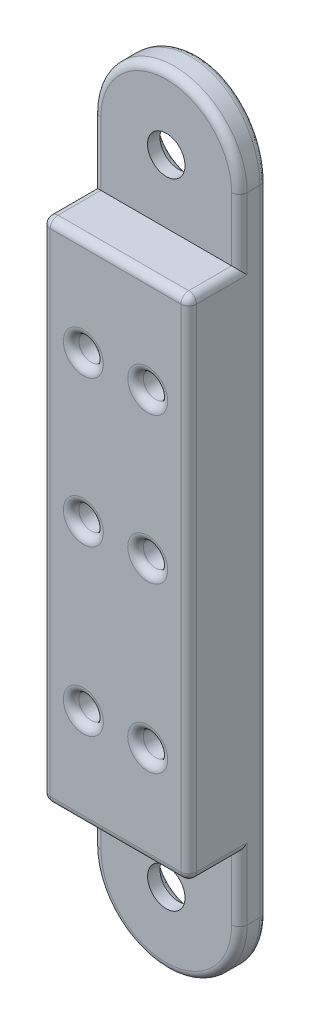
SolidWorks part; units mm, degrees
material "Nylon 101"
ref_plane "Front Plane" through (0, 0, 0) normal (0, 0, 1) x (1, 0, 0)
ref_plane "Top Plane" through (0, 0, 0) normal (0, 1, 0) x (1, 0, 0)
ref_plane "Right Plane" through (0, 0, 0) normal (1, 0, 0) x (0, 0, -1)
sketch "Sketch1" plane through (0, 0, 0) normal (0, 1, 0) x (1, 0, 0)
  line L1 (-4.1913, 1.27) -> (5.3337, 1.27)
  line L2 (-4.1913, 1.27) -> (-4.1913, 6.35)
  line L4 (5.3337, 1.27) -> (5.3337, 6.35)
  arc A0 (-4.1913, 6.35) -> (5.3337, 6.35) centre (0.5712, -31.4512) cw
  dimension "D3" = 38.1
  dimension "D1" = 9.525
  dimension "D2" = 5.08
extrude "Main profile" add sketch "Sketch1" along normal blind 50.8
sketch "Sketch2" plane through (0, 0, -1.27) normal (0, 0, 1) x (1, 0, 0)
  line L0 (-4.1913, 50.8) -> (-4.1913, 0) construction
  line L1 (5.3337, 50.8) -> (5.3337, 0) construction
  line L2 (-4.1913, 50.8) -> (5.3337, 50.8) construction
  line L3 (-4.1913, 0) -> (5.3337, 0) construction
  line L4 (-4.1913, 46.0375) -> (-4.1913, 4.7625)
  line L5 (5.3337, 46.0375) -> (5.3337, 4.7625)
  line L10 (-4.1913, 0) -> (5.3337, 0)
  line L11 (5.3337, 0) -> (5.3337, 50.8)
  line L12 (5.3337, 50.8) -> (-4.1913, 50.8)
  line L13 (-4.1913, 50.8) -> (-4.1913, 0)
  line L14 (-4.1913, 0) -> (5.3337, 0)
  line L15 (5.3337, 0) -> (5.3337, 50.8)
  line L16 (5.3337, 50.8) -> (-4.1913, 50.8)
  line L17 (-4.1913, 50.8) -> (-4.1913, 0)
  arc A0 (-4.1913, 46.0375) -> (5.3337, 46.0375) centre (0.5712, 46.0375) cw
  arc A1 (5.3337, 4.7625) -> (-4.1913, 4.7625) centre (0.5712, 4.7625) cw
  line M9 (-4.1913, 0) -> (5.3337, 0)
  line M10 (5.3337, 0) -> (5.3337, 50.8)
  line M11 (5.3337, 50.8) -> (-4.1913, 50.8)
  line M12 (-4.1913, 50.8) -> (-4.1913, 0)
  dimension "D2" = 4.7625
  dimension "D1" = 0
extrude "End rounds" cut sketch "Sketch2" against normal blind 25.4 contours A0 L16 M12 | A0 M11 M10 | A1 L14 M10 | A1 M9 M12
sketch "Sketch3" plane through (-4.1913, 0, 0) normal (-1, 0, 0) x (0, 0, 1)
  line L1 (-1.27, 46.0375) -> (-1.27, 50.8) construction
  line L4 (-1.27, 4.7625) -> (-1.27, 46.0375)
  line L7 (-1.27, 46.0375) -> (-6.35, 46.0375)
  line L8 (-1.27, 4.7625) -> (-1.27, 46.0375)
  line L12 (-1.27, 0) -> (-1.27, 4.7625) construction
  line L14 (-4.572, 25.4) -> (-1.27, 25.4) construction
  line L15 (-1.27, 46.0375) -> (-1.27, 50.8)
  line L17 (-4.572, 41.91) -> (-1.27, 41.91)
  line L18 (-1.27, 0) -> (-1.27, 4.7625)
  line L19 (-1.27, 8.89) -> (-4.572, 8.89)
  line L20 (-2.921, 8.89) -> (-2.921, 41.91) construction
  line L21 (-1.27, 50.8) -> (-4.572, 50.8)
  line L22 (-1.27, 50.8) -> (-1.27, 0)
  line L23 (-1.27, 0) -> (-4.572, 0)
  line L24 (-4.572, 50.8) -> (-4.572, 0)
  line L29 (-6.35, 4.7625) -> (-1.27, 4.7625)
  line L31 (-6.35, 46.0375) -> (-6.35, 4.7625)
  line L32 (-6.35, 46.0375) -> (-6.35, 4.7625)
  spline S0 degree 2 poles (-6.6488, 50.8) (-6.35, 48.4094) (-6.35, 46.0375) knots 0 0 0 0.468627 0.468627 0.468627 weights 0.033338 0.035569 0.037801 construction
  spline S1 degree 2 poles (-6.35, 4.7625) (-6.35, 2.3906) (-6.6488, 0) knots 0.468627 0.468627 0.468627 1 1 1 weights 0.037801 0.040332 0.042863 construction
  spline S2 degree 2 poles (-6.6488, 50.8) (-6.35, 48.4094) (-6.35, 46.0375) knots 0 0 0 0.468627 0.468627 0.468627 weights 0.033338 0.035569 0.037801
  spline S3 degree 2 poles (-6.35, 4.7625) (-6.35, 2.3906) (-6.6488, 0) knots 0.468627 0.468627 0.468627 1 1 1 weights 0.037801 0.040332 0.042863
  point P19 (-2.921, 25.4)
  line M11 (-1.27, 4.7625) -> (-1.27, 46.0375)
  line M12 (-1.27, 46.0375) -> (-6.35, 46.0375)
  line M14 (-6.35, 4.7625) -> (-1.27, 4.7625)
  dimension "D2" = 3.302
  dimension "D3" = 8.89
  dimension "D1" = 0
extrude "Locating Flange" cut sketch "Sketch3" against normal through all contours L24 L23 L18 M14 | L19 L24 M14 M11 | L24 L17 L8 M12 | L21 L24 L15 M12
ref_plane "Top Surface" through (0, 0, -6.6488) normal (0, 0, -1) x (-1, 0, 0)
sketch "Sketch4" plane through (0, 0, -6.6488) normal (0, 0, -1) x (-1, 0, 0)
  line L0 (-0.5712, 18.542) -> (-0.5712, 32.258) construction
  line L1 (-2.6827, 38.735) -> (1.5403, 38.735)
  line L2 (-5.3337, 46.0375) -> (-5.3337, 4.7625)
  line L6 (-3.8097, 37.608) -> (-3.8097, 33.385)
  line L7 (-2.6827, 32.258) -> (1.5403, 32.258)
  line L8 (2.6673, 37.608) -> (2.6673, 33.385)
  line L9 (-2.6827, 29.226) -> (1.5403, 29.226)
  line L14 (-3.8097, 28.099) -> (-3.8097, 23.876)
  line L16 (-2.6827, 22.749) -> (1.5403, 22.749)
  line L18 (4.1913, 8.89) -> (4.1913, 41.91)
  line L19 (-5.3337, 8.89) -> (4.1913, 8.89)
  line L20 (-5.3337, 41.91) -> (-5.3337, 8.89)
  line L21 (4.1913, 41.91) -> (-5.3337, 41.91)
  line L22 (4.1913, 8.89) -> (4.1913, 41.91)
  line L23 (-5.3337, 8.89) -> (4.1913, 8.89)
  line L24 (-5.3337, 41.91) -> (-5.3337, 8.89)
  line L25 (4.1913, 41.91) -> (-5.3337, 41.91)
  line L26 (2.6673, 28.099) -> (2.6673, 23.876)
  line L27 (-2.6827, 18.542) -> (1.5403, 18.542)
  line L28 (-3.8097, 17.415) -> (-3.8097, 13.192)
  line L29 (-2.6827, 12.065) -> (1.5403, 12.065)
  line L30 (2.6673, 17.415) -> (2.6673, 13.192)
  line L31 (-5.3337, 25.4) -> (4.1913, 25.4) construction
  line L34 (-5.3337, 46.0375) -> (-5.3337, 4.7625)
  line L36 (4.1913, 4.7625) -> (4.1913, 46.0375)
  line L37 (4.1913, 4.7625) -> (4.1913, 46.0375)
  arc A0 (1.5403, 12.065) -> (2.6673, 13.192) centre (1.5403, 13.192) ccw
  arc A1 (-3.8097, 13.192) -> (-2.6827, 12.065) centre (-2.6827, 13.192) ccw
  arc A2 (4.1913, 46.0375) -> (-5.3337, 46.0375) centre (-0.5712, 46.0375) ccw
  arc A3 (4.1913, 46.0375) -> (-5.3337, 46.0375) centre (-0.5712, 46.0375) ccw
  arc A6 (-5.3337, 4.7625) -> (4.1913, 4.7625) centre (-0.5712, 4.7625) ccw
  arc A7 (-5.3337, 4.7625) -> (4.1913, 4.7625) centre (-0.5712, 4.7625) ccw
  arc A8 (1.5403, 18.542) -> (2.6673, 17.415) centre (1.5403, 17.415) cw
  arc A9 (-2.6827, 18.542) -> (-3.8097, 17.415) centre (-2.6827, 17.415) ccw
  arc A10 (1.5403, 38.735) -> (2.6673, 37.608) centre (1.5403, 37.608) cw
  arc A11 (1.5403, 32.258) -> (2.6673, 33.385) centre (1.5403, 33.385) ccw
  arc A12 (-3.8097, 33.385) -> (-2.6827, 32.258) centre (-2.6827, 33.385) ccw
  arc A13 (1.5403, 22.749) -> (2.6673, 23.876) centre (1.5403, 23.876) ccw
  arc A14 (-2.6827, 29.226) -> (-3.8097, 28.099) centre (-2.6827, 28.099) ccw
  arc A15 (-3.8097, 23.876) -> (-2.6827, 22.749) centre (-2.6827, 23.876) ccw
  arc A16 (1.5403, 29.226) -> (2.6673, 28.099) centre (1.5403, 28.099) cw
  arc A17 (-2.6827, 38.735) -> (-3.8097, 37.608) centre (-2.6827, 37.608) ccw
  point P23 (-0.5712, 18.542)
  point P27 (-0.5712, 25.4)
  point P28 (-0.5712, 29.226)
  point P57 (-0.5712, 25.4)
  dimension "D6" = 1.127
  dimension "D4" = 3.175
  dimension "D5" = 3.175
  dimension "D7" = 6.477
  dimension "D1" = 0
  dimension "D3" = 0
extrude "Button Pockets" cut sketch "Sketch4" against normal blind 3.81 contours L16 L0 L9 L14 | L0 L16 L26 L9 | L30 L27 L28 L29 | L6 A12 L7 A11 L8 A10 L1 A17
sketch "Hole Locations" plane through (0, 0, -6.6488) normal (0, 0, -1) x (-1, 0, 0)
  line L2 (-5.3337, 46.0375) -> (-5.3337, 4.7625)
  line L6 (-5.3337, 46.0375) -> (-5.3337, 4.7625)
  line L8 (4.1913, 4.7625) -> (4.1913, 46.0375)
  line L9 (4.1913, 4.7625) -> (4.1913, 46.0375)
  arc A2 (4.1913, 46.0375) -> (-5.3337, 46.0375) centre (-0.5712, 46.0375) ccw
  arc A3 (-5.3337, 4.7625) -> (4.1913, 4.7625) centre (-0.5712, 4.7625) ccw
  arc A4 (4.1913, 46.0375) -> (-5.3337, 46.0375) centre (-0.5712, 46.0375) ccw
  arc A5 (-5.3337, 4.7625) -> (4.1913, 4.7625) centre (-0.5712, 4.7625) ccw
  point P5 (-0.5712, 46.0375)
  point P8 (-0.5712, 4.7625)
  dimension "D1" = 0
hole_wizard "CBORE for #2 Socket Head Cap Screw1" positions "Sketch7" profile "Sketch9" counterbore size "#2" standard "ANSI Inch" end condition through all
sketch "Sketch7" plane through (0, 0, -6.6488) normal (0, 0, -1) x (-1, 0, 0)
  point P0 (-0.5712, 46.0375)
  point P3 (-0.5712, 4.7625)
sketch "Sketch9" plane through (0.5712, 46.0375, -6.6488) normal (1, 0, 0) x (0, 1, 0)
  line L0 (0, 0) -> (0, 5.3788)
  line L1 (0, 5.3788) -> (1.2192, 5.3788)
  line L3 (1.2192, 5.3788) -> (1.2192, 1.27)
  line L4 (1.2192, 1.27) -> (2.286, 1.27)
  line L5 (2.286, 1.27) -> (2.286, 0)
  line L7 (2.286, 0) -> (0, 0)
  line L11 (0, -6.35) -> (0, 107.95) construction
  dimension "Thru Hole Dia." = 2.4384
  dimension "Thru Hole Depth" = 5.3788
  dimension "C'Bore Dia." = 4.572
  dimension "C'Bore Depth" = 1.27
sketch "Sketch13" plane through (0, 0, -1.27) normal (0, 0, 1) x (1, 0, 0)
  line L0 (-1.5403, 18.542) -> (2.6827, 18.542) construction
  line L1 (3.8097, 17.415) -> (3.8097, 13.192) construction
  line L2 (2.6827, 12.065) -> (-1.5403, 12.065) construction
  line L3 (-2.6673, 13.192) -> (-2.6673, 17.415) construction
  line L4 (-1.5403, 29.226) -> (2.6827, 29.226) construction
  line L5 (3.8097, 28.099) -> (3.8097, 23.876) construction
  line L6 (2.6827, 22.749) -> (-1.5403, 22.749) construction
  line L7 (-2.6673, 23.876) -> (-2.6673, 28.099) construction
  line L8 (3.8097, 37.608) -> (3.8097, 33.385) construction
  line L9 (2.6827, 32.258) -> (-1.5403, 32.258) construction
  line L10 (-2.6673, 33.385) -> (-2.6673, 37.608) construction
  line L11 (-1.5403, 38.735) -> (2.6827, 38.735) construction
  line L12 (-4.1913, 41.91) -> (-4.1913, 8.89) construction
  line L13 (-4.1913, 8.89) -> (5.3337, 8.89) construction
  line L14 (5.3337, 8.89) -> (5.3337, 41.91) construction
  line L15 (5.3337, 41.91) -> (-4.1913, 41.91) construction
  line L16 (-1.5403, 18.542) -> (2.6827, 18.542)
  line L17 (3.8097, 17.415) -> (3.8097, 13.192)
  line L18 (2.6827, 12.065) -> (-1.5403, 12.065)
  line L19 (-2.6673, 13.192) -> (-2.6673, 17.415)
  line L20 (-1.5403, 29.226) -> (2.6827, 29.226)
  line L21 (3.8097, 28.099) -> (3.8097, 23.876)
  line L22 (2.6827, 22.749) -> (-1.5403, 22.749)
  line L23 (-2.6673, 23.876) -> (-2.6673, 28.099)
  line L24 (3.8097, 37.608) -> (3.8097, 33.385)
  line L25 (2.6827, 32.258) -> (-1.5403, 32.258)
  line L26 (-2.6673, 33.385) -> (-2.6673, 37.608)
  line L27 (-1.5403, 38.735) -> (2.6827, 38.735)
  line L28 (-4.1913, 41.91) -> (-4.1913, 8.89)
  line L29 (-4.1913, 8.89) -> (5.3337, 8.89)
  line L30 (5.3337, 8.89) -> (5.3337, 41.91)
  line L31 (5.3337, 41.91) -> (-4.1913, 41.91)
  line L32 (-1.5243, 35.4965) -> (2.6667, 35.4965) construction
  arc A0 (3.8097, 17.415) -> (2.6827, 18.542) centre (2.6827, 17.415) ccw construction
  arc A1 (2.6827, 12.065) -> (3.8097, 13.192) centre (2.6827, 13.192) ccw construction
  arc A2 (-2.6673, 13.192) -> (-1.5403, 12.065) centre (-1.5403, 13.192) ccw construction
  arc A3 (-1.5403, 18.542) -> (-2.6673, 17.415) centre (-1.5403, 17.415) ccw construction
  arc A4 (-1.5403, 29.226) -> (-2.6673, 28.099) centre (-1.5403, 28.099) ccw construction
  arc A5 (3.8097, 28.099) -> (2.6827, 29.226) centre (2.6827, 28.099) ccw construction
  arc A6 (2.6827, 22.749) -> (3.8097, 23.876) centre (2.6827, 23.876) ccw construction
  arc A7 (-2.6673, 23.876) -> (-1.5403, 22.749) centre (-1.5403, 23.876) ccw construction
  arc A8 (3.8097, 37.608) -> (2.6827, 38.735) centre (2.6827, 37.608) ccw construction
  arc A9 (2.6827, 32.258) -> (3.8097, 33.385) centre (2.6827, 33.385) ccw construction
  arc A10 (-2.6673, 33.385) -> (-1.5403, 32.258) centre (-1.5403, 33.385) ccw construction
  arc A11 (-1.5403, 38.735) -> (-2.6673, 37.608) centre (-1.5403, 37.608) ccw construction
  arc A12 (3.8097, 17.415) -> (2.6827, 18.542) centre (2.6827, 17.415) ccw
  arc A13 (2.6827, 12.065) -> (3.8097, 13.192) centre (2.6827, 13.192) ccw
  arc A14 (-2.6673, 13.192) -> (-1.5403, 12.065) centre (-1.5403, 13.192) ccw
  arc A15 (-1.5403, 18.542) -> (-2.6673, 17.415) centre (-1.5403, 17.415) ccw
  arc A16 (-1.5403, 29.226) -> (-2.6673, 28.099) centre (-1.5403, 28.099) ccw
  arc A17 (3.8097, 28.099) -> (2.6827, 29.226) centre (2.6827, 28.099) ccw
  arc A18 (2.6827, 22.749) -> (3.8097, 23.876) centre (2.6827, 23.876) ccw
  arc A19 (-2.6673, 23.876) -> (-1.5403, 22.749) centre (-1.5403, 23.876) ccw
  arc A20 (3.8097, 37.608) -> (2.6827, 38.735) centre (2.6827, 37.608) ccw
  arc A21 (2.6827, 32.258) -> (3.8097, 33.385) centre (2.6827, 33.385) ccw
  arc A22 (-2.6673, 33.385) -> (-1.5403, 32.258) centre (-1.5403, 33.385) ccw
  arc A23 (-1.5403, 38.735) -> (-2.6673, 37.608) centre (-1.5403, 37.608) ccw
  point P4 (-1.5243, 35.4965)
  point P5 (2.6667, 35.4965)
  point P9 (2.6667, 25.9875)
  point P10 (2.6667, 15.3035)
  point P14 (-1.5243, 15.3035)
  point P15 (-1.5243, 25.9875)
  point P18 (0.5712, 35.4965)
  point P19 (0.5712, 41.91)
  point P27 (3.8097, 25.9875)
  point P37 (3.8097, 15.3035)
  point P39 (3.8097, 35.4965)
  dimension "D1" = 4.191
hole_wizard "1/16 (0.0625) Diameter Hole1" positions "Sketch14" profile "Sketch16" hole size "1/16" standard "ANSI Inch" end condition through all
sketch "Sketch14" plane through (0, 0, -1.27) normal (0, 0, 1) x (1, 0, 0)
  point P0 (-1.5243, 35.4965)
  point P3 (2.6667, 35.4965)
  point P6 (2.6667, 25.9875)
  point P9 (-1.5243, 25.9875)
  point P12 (-1.5243, 15.3035)
  point P15 (2.6667, 15.3035)
sketch "Sketch16" plane through (-1.5243, 35.4965, -1.27) normal (1, 0, 0) x (0, -1, 0)
  line L0 (0, 0) -> (0, 5.3788)
  line L1 (0, 5.3788) -> (0.7937, 5.3788)
  line L2 (0.7937, 5.3788) -> (0.7937, 0)
  line L5 (0.7937, 0) -> (0, 0)
  line L11 (0, -6.35) -> (0, 107.95) construction
  dimension "Thru Hole Dia." = 1.5875
  dimension "Thru Hole Depth" = 5.3788
fillet "Fillet1" radius 0.508 26 edges at (-4.1913, 43.9737, -4.572) (0.5712, 50.8, -4.572) (0.5712, 50.8, -6.6488) (-4.1913, 25.4, -6.35) (0.5712, 0, -6.6488) (-4.1913, 6.8262, -4.572) (0.5712, 0, -4.572) (2.797, 46.5587, -6.5838) (5.3337, 25.4, -1.27) (5.3337, 41.91, -2.921) (5.3337, 43.9737, -4.572) (5.3337, 25.4, -6.35) (5.3337, 6.8262, -4.572) (5.3337, 8.89, -2.921) (-4.1913, 8.89, -2.921) (-4.1913, 41.91, -2.921) (-0.7306, 15.3035, -1.27) (3.4604, 15.3035, -1.27) (-0.7306, 25.9875, -1.27) (3.4604, 25.9875, -1.27) (3.4604, 35.4965, -1.27) (-0.7306, 35.4965, -1.27) (0.5712, 41.91, -1.27) (-4.1913, 25.4, -1.27) (0.5712, 8.89, -1.27) (2.797, 5.2837, -6.5838)
